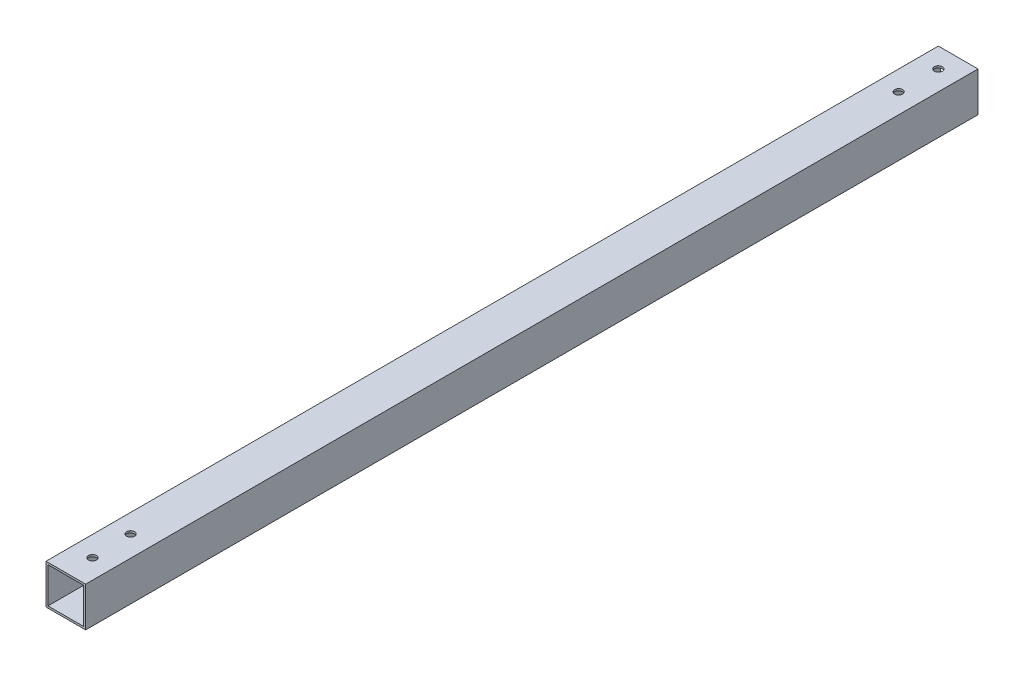
SolidWorks part; units mm, degrees
ref_plane "前视基准面" through (0, 0, 0) normal (0, 0, 1) x (1, 0, 0)
ref_plane "上视基准面" through (0, 0, 0) normal (0, 1, 0) x (1, 0, 0)
ref_plane "右视基准面" through (0, 0, 0) normal (1, 0, 0) x (0, 0, -1)
other "Configuration Table"
sketch "草图1" plane through (0, 0, 0) normal (0, 0, 1) x (1, 0, 0)
  line L1 (-9, -9) -> (9, -9)
  line L2 (-9, -9) -> (-9, 9)
  line L3 (-9, 9) -> (9, 9)
  line L4 (9, -9) -> (9, 9)
  line L5 (-9, -9) -> (9, 9) construction
  line L6 (-9, 9) -> (9, -9) construction
  line L7 (10, 10) -> (-10, 10)
  line L8 (10, 10) -> (10, -10)
  line L9 (10, -10) -> (-10, -10)
  line L10 (-10, 10) -> (-10, -10)
  line L11 (10, 10) -> (-10, -10) construction
  line L12 (10, -10) -> (-10, 10) construction
  point P0 (0, 0)
  point P5 (0, 0)
  dimension "D1" = 18
  dimension "D2" = 20
extrude "凸台-拉伸1" add sketch "草图1" along normal blind 450
sketch "草图2" plane through (0, 10, 0) normal (0, 1, 0) x (1, 0, 0)
  line L0 (0, -1000) -> (0, 49000) construction
  line L1 (10, 0) -> (-10, 0) construction
  circle A0 centre (0, -10) radius 2
  circle A1 centre (0, -30) radius 2
  dimension "D1" = 4
  dimension "D2" = 4
  dimension "D3" = 10
  dimension "D4" = 20
extrude "切除-拉伸1" cut sketch "草图2" against normal blind 430
sketch "草图3" plane through (0, 10, 0) normal (0, 1, 0) x (1, 0, 0)
  circle A0 centre (0.2009, -436.7209) radius 2 construction
  circle A1 centre (-0.5729, -416.7359) radius 2 construction
  circle A2 centre (0.2009, -436.7209) radius 2
  circle A3 centre (-0.5729, -416.7359) radius 2
extrude "切除-拉伸2" cut sketch "草图3" against normal blind 430
